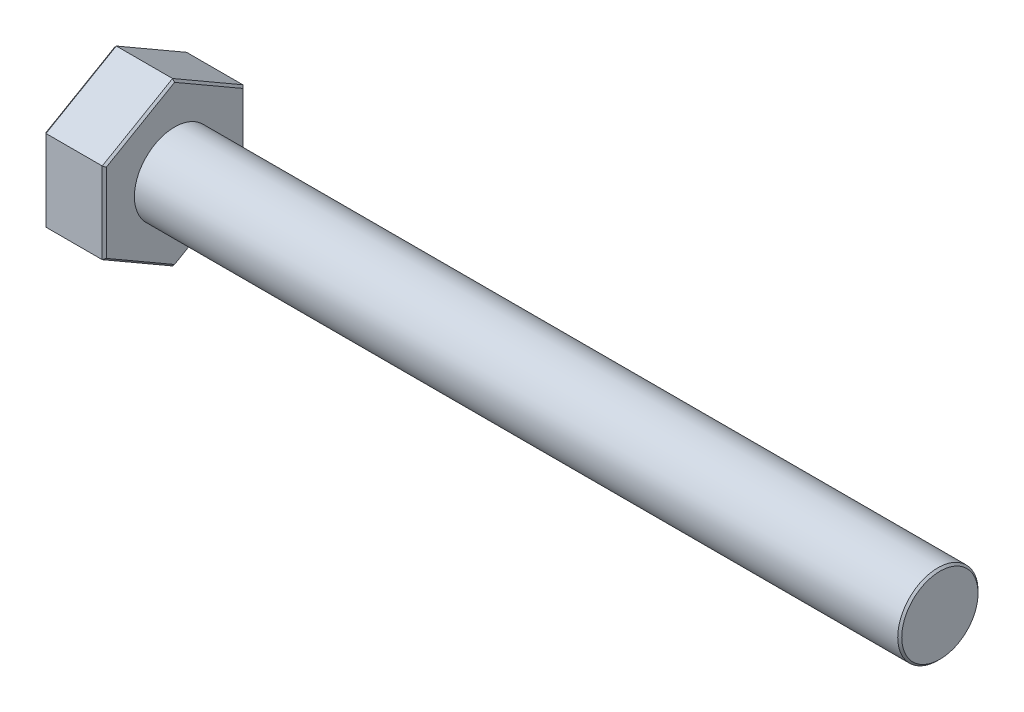
SolidWorks part; units mm, degrees
material "CRCA"
ref_plane "Front Plane" through (0, 0, 0) normal (0, 0, 1) x (1, 0, 0)
ref_plane "Top Plane" through (0, 0, 0) normal (0, 1, 0) x (1, 0, 0)
ref_plane "Right Plane" through (0, 0, 0) normal (1, 0, 0) x (0, 0, -1)
sketch "Sketch1" plane through (0, 0, 0) normal (0, 0, 1) x (1, 0, 0)
  line L0 (-15.5547, 0) -> (34.7607, 0) construction
  line L1 (0, 0) -> (0, 2)
  line L2 (0, 2) -> (38.1, 2)
  line L3 (38.1, 2) -> (38.1, 0)
  line L4 (38.1, 0) -> (0, 0)
  dimension "D1" = 4
  dimension "D2" = 38.1
revolve "Revolve1" add sketch "Sketch1" angle 360 about L0
cosmetic thread "Cosmetic Thread1" [suppressed] parameters "D1"=14, "D2"=3.22
sketch "Sketch2" plane through (0, 0, 0) normal (-1, 0, 0) x (0, 0, 1)
  line L1 (0, 4.0415) -> (-3.5, 2.0207)
  line L2 (-3.5, 2.0207) -> (-3.5, -2.0207)
  line L3 (-3.5, -2.0207) -> (0, -4.0415)
  line L4 (0, -4.0415) -> (3.5, -2.0207)
  line L5 (3.5, -2.0207) -> (3.5, 2.0207)
  line L6 (3.5, 2.0207) -> (0, 4.0415)
  circle A0 centre (0, 0) radius 3.5 construction
  dimension "D1" = 7
extrude "Boss-Extrude1" add sketch "Sketch2" along normal blind 3
chamfer "Chamfer1" distance 0.1 angle 45 12 edges at (-3, 0, 3.5) (-3, -3.0311, 1.75) (-3, -3.0311, -1.75) (-3, 0, -3.5) (-3, 3.0311, -1.75) (-3, 3.0311, 1.75) (0, -3.0311, -1.75) (0, -3.0311, 1.75) (0, 0, 3.5) (0, 3.0311, 1.75) (0, 3.0311, -1.75) (0, 0, -3.5)
chamfer "Chamfer2" distance 0.1 angle 45 1 edges at (38.1, 0, 2)
